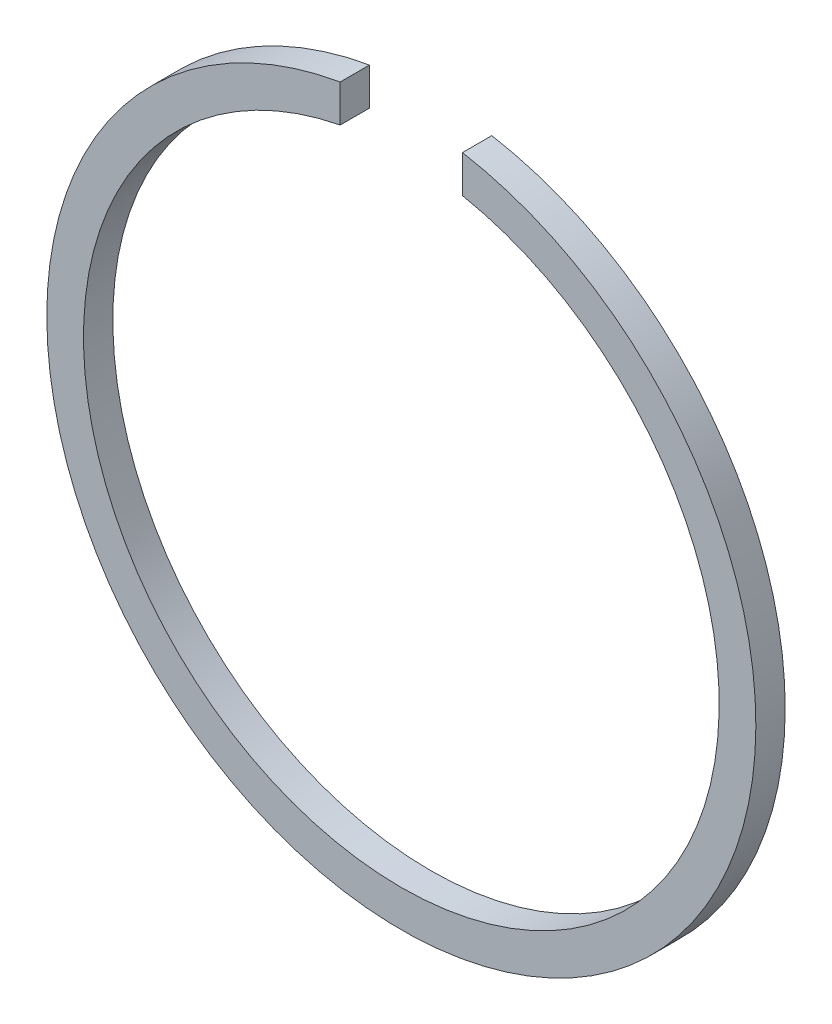
SolidWorks part; units mm, degrees
material "Cast Carbon Steel"
ref_plane "Front Plane" through (0, 0, 0) normal (0, 0, 1) x (1, 0, 0)
ref_plane "Top Plane" through (0, 0, 0) normal (0, 1, 0) x (1, 0, 0)
ref_plane "Right Plane" through (0, 0, 0) normal (1, 0, 0) x (0, 0, -1)
sketch "Sketch1" plane through (0, 0, 0) normal (0, 0, 1) x (1, 0, 0)
  line L1 (2.5, 12.7574) -> (2.5, 14.2829)
  line L2 (-2.5, 12.7574) -> (-2.5, 14.2829)
  arc A0 (-2.5, 14.2829) -> (2.5, 14.2829) centre (0, 0) ccw
  arc A1 (-2.5, 12.7574) -> (2.5, 12.7574) centre (0, 0) ccw
  circle A2 centre (0, 0) radius 14.5 construction
  circle A3 centre (0, 0) radius 13 construction
  dimension "D1" = 29
  dimension "D2" = 1.5
extrude "Boss-Extrude1" add sketch "Sketch1" along normal blind 1.2
